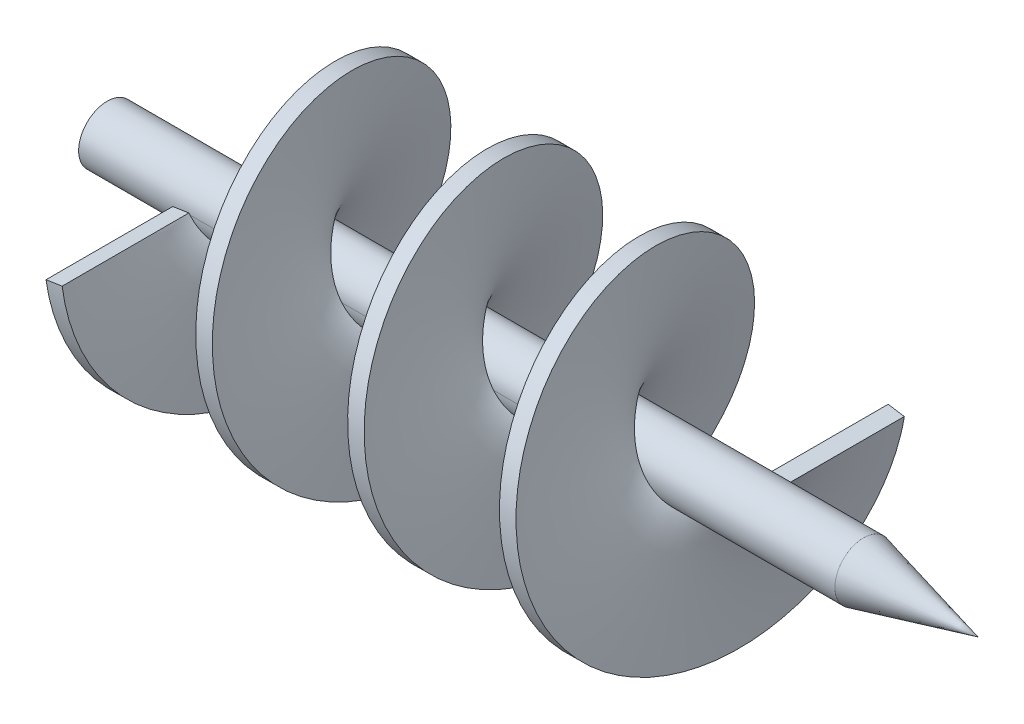
SolidWorks part; units mm, degrees
material "Ti-5Al-2.5Sn Annealed (SS)"
ref_plane "Front Plane" through (0, 0, 0) normal (0, 0, 1) x (1, 0, 0)
ref_plane "Top Plane" through (0, 0, 0) normal (0, 1, 0) x (1, 0, 0)
ref_plane "Right Plane" through (0, 0, 0) normal (1, 0, 0) x (0, 0, -1)
sketch "Sketch1" plane through (0, 0, 0) normal (0, 0, 1) x (1, 0, 0)
  line L0 (-23.9143, 0) -> (18.6857, 0)
  line L1 (18.6857, 0) -> (13.0857, 1.4)
  line L2 (13.0857, 1.4) -> (-23.9143, 1.4)
  line L3 (-23.9143, 1.4) -> (-23.9143, 0)
  dimension "D1" = 5.6
  dimension "D2" = 42.6
  dimension "D3" = 1.4
revolve "Revolve1" add sketch "Sketch1" angle 360 about L0
ref_plane "Plane1" through (-18.9143, 0, 0) normal (-1, 0, 0) x (0, 0, 1)
sketch "Sketch2" plane through (-18.9143, 0, 0) normal (-1, 0, 0) x (0, 0, 1)
  circle A0 centre (0, 0) radius 7.6
  dimension "D1" = 15.2
curve "Helix/Spiral1" pitch 7.4286 height 26 turns 3.5
ref_plane "Plane2" through (-18.9143, 0, 7.6) normal (0.1537, -0.9881, 0) x (-0.9881, -0.1537, 0)
sketch "Sketch3" plane through (-18.9143, 0, 7.6) normal (0.1537, -0.9881, 0) x (-0.9881, -0.1537, 0)
  line L0 (0.4, 7.6) -> (-0.4, 7.6)
  line L1 (0.4, 7.6) -> (0.4, 0)
  line L2 (-0.4, 7.6) -> (-0.4, 0)
  line L3 (0.4, 0) -> (-0.4, 0)
  point P0 (0, 0)
  dimension "D1" = 0.8
  dimension "D2" = 7.6
sweep "Sweep1" add profiles "Sketch3" path "Helix/Spiral1"
